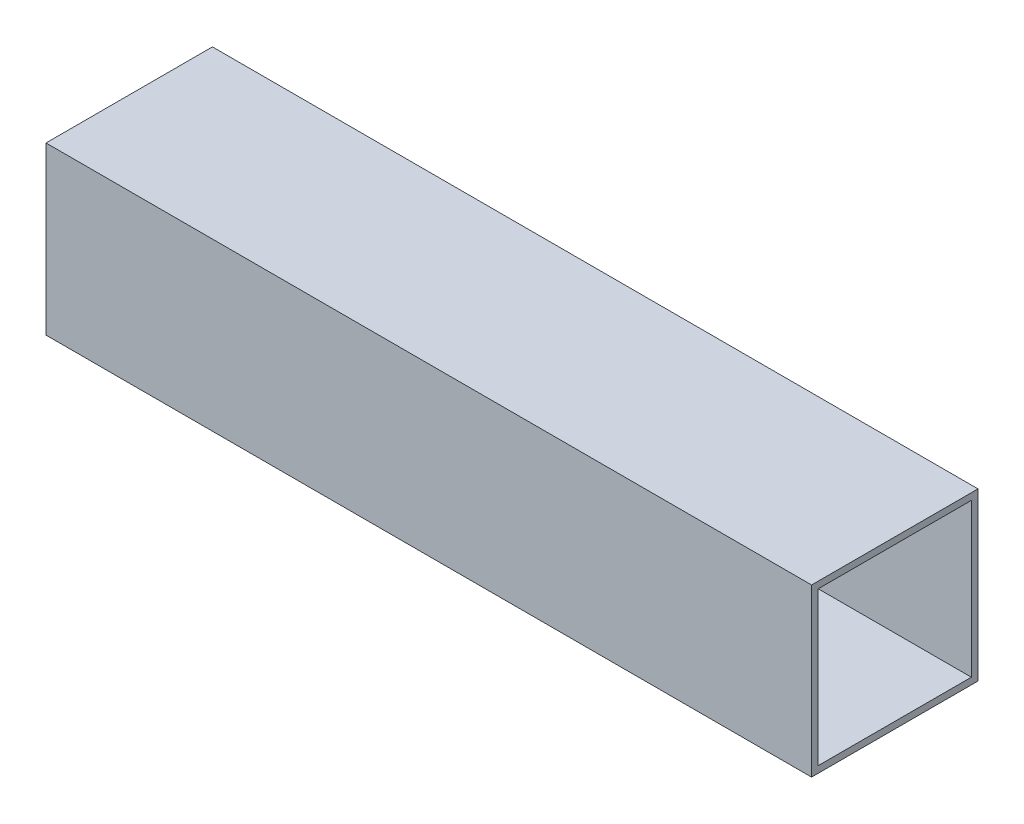
SolidWorks part; units mm, degrees
ref_plane "Front Plane" through (0, 0, 0) normal (0, 0, 1) x (1, 0, 0)
ref_plane "Top Plane" through (0, 0, 0) normal (0, 1, 0) x (1, 0, 0)
ref_plane "Right Plane" through (0, 0, 0) normal (1, 0, 0) x (0, 0, -1)
sketch "Sketch1" plane through (0, 0, 0) normal (1, 0, 0) x (0, 0, -1)
  line L1 (12.5, -12.5) -> (-12.5, -12.5)
  line L2 (12.5, -12.5) -> (12.5, 12.5)
  line L3 (12.5, 12.5) -> (-12.5, 12.5)
  line L4 (-12.5, -12.5) -> (-12.5, 12.5)
  line L5 (12.5, -12.5) -> (-12.5, 12.5) construction
  line L6 (12.5, 12.5) -> (-12.5, -12.5) construction
  line L7 (11.5, -11.5) -> (-11.5, -11.5)
  line L8 (11.5, -11.5) -> (11.5, 11.5)
  line L9 (11.5, 11.5) -> (-11.5, 11.5)
  line L10 (-11.5, -11.5) -> (-11.5, 11.5)
  line L11 (11.5, -11.5) -> (-11.5, 11.5) construction
  line L12 (11.5, 11.5) -> (-11.5, -11.5) construction
  point P0 (0, 0)
  point P6 (0, 0)
  dimension "D1" = 25
  dimension "D2" = 1
extrude "Boss-Extrude1" add sketch "Sketch1" along normal blind 115
